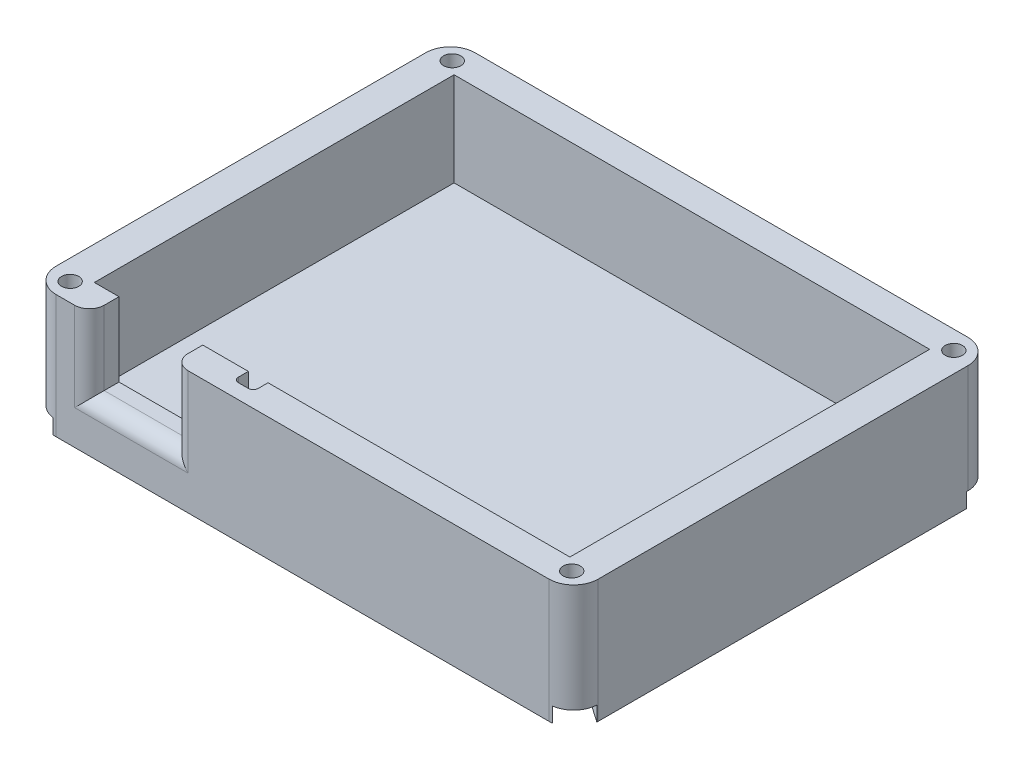
SolidWorks part; units mm, degrees
ref_plane "Front Plane" through (0, 0, 0) normal (0, 0, 1) x (1, 0, 0)
ref_plane "Top Plane" through (0, 0, 0) normal (0, 1, 0) x (1, 0, 0)
ref_plane "Right Plane" through (0, 0, 0) normal (1, 0, 0) x (0, 0, -1)
sketch "Sketch1" plane through (0, 0, 0) normal (0, 1, 0) x (1, 0, 0)
  line L1 (-55, 42.5) -> (55, 42.5)
  line L2 (-55, 42.5) -> (-55, -42.5)
  line L3 (-55, -42.5) -> (55, -42.5)
  line L4 (55, 42.5) -> (55, -42.5)
  line L5 (-55, 42.5) -> (55, -42.5) construction
  line L6 (-55, -42.5) -> (55, 42.5) construction
  point P0 (0, 0)
  dimension "D1" = 85
  dimension "D2" = 110
extrude "Base" add sketch "Sketch1" along normal blind 25
fillet "Fillet1" radius 5 4 edges at (-55, 12.5, -42.5) (55, 12.5, 42.5) (55, 12.5, -42.5) (-55, 12.5, 42.5)
sketch "Sketch2" plane through (0, 25, 0) normal (0, 1, 0) x (1, 0, 0)
  line L1 (-48.25, 36.5) -> (48.25, 36.5)
  line L2 (-48.25, 36.5) -> (-48.25, -36.5)
  line L3 (-48.25, -36.5) -> (48.25, -36.5)
  line L4 (48.25, 36.5) -> (48.25, -36.5)
  line L5 (-48.25, 36.5) -> (48.25, -36.5) construction
  line L6 (-48.25, -36.5) -> (48.25, 36.5) construction
  point P0 (0, 0)
  dimension "D1" = 73
  dimension "D2" = 96.5
extrude "Basket" cut sketch "Sketch2" against normal blind 19
sketch "Sketch3" plane through (0, 25, 0) normal (0, 1, 0) x (1, 0, 0)
  line L0 (-55, -12.0792) -> (-15, -12.0792) construction
  line L1 (-55, 37.5) -> (-55, -37.5) construction
  line L2 (-15, -12.0792) -> (-15, -36.5) construction
  line L3 (-48.25, -36.5) -> (48.25, -36.5) construction
  line L4 (-48.25, 36.5) -> (-48.25, -36.5) construction
  line L5 (-17, -33.5) -> (-13, -33.5)
  line L6 (-17, -33.5) -> (-17, -39.5)
  line L7 (-17, -39.5) -> (-13, -39.5)
  line L8 (-13, -33.5) -> (-13, -39.5)
  line L9 (-17, -33.5) -> (-13, -39.5) construction
  line L10 (-17, -39.5) -> (-13, -33.5) construction
  dimension "D2" = 4
  dimension "D3" = 6
  dimension "D4" = 33.25
extrude "Wire Channel" cut sketch "Sketch3" against normal up to surface (19 mm away) up to face at (0, 6, 0)
fillet "Wire Channel Rounding" radius 1 2 edges at (-13, 15.5, 39.5) (-17, 15.5, 39.5)
ref_plane "Battery Pack Left Side Wall" through (-48.25, 0, 0) normal (1, 0, 0) x (0, 0, -1)
sketch "Sketch5" plane through (0, 0, 42.5) normal (0, 0, 1) x (1, 0, 0)
  line L0 (-48.25, 25) -> (-43.25, 25) construction
  line L1 (-48.25, -9.9) -> (-48.25, 9.9) construction
  line L2 (-50, 25) -> (50, 25) construction
  line L5 (-43.25, 25) -> (-26.25, 25)
  line L6 (-43.25, 25) -> (-43.25, 10)
  line L7 (-43.25, 10) -> (-26.25, 10)
  line L8 (-26.25, 25) -> (-26.25, 10)
  dimension "D1" = 5
  dimension "D3" = 17
  dimension "D4" = 15
extrude "Switch Cut-out" cut sketch "Sketch5" against normal up to next
fillet "Switch Cut-out Rounding" radius 3 3 edges at (-43.25, 17.5, 42.5) (-34.75, 10, 42.5) (-26.25, 17.5, 42.5)
sketch "Sketch14" plane through (0, 25, 0) normal (0, 1, 0) x (1, 0, 0)
  line L0 (-53.5355, 41.0355) -> (-48.25, 36.5) construction
  line L1 (53.5355, 41.0355) -> (48.25, 36.5) construction
  line L2 (53.5355, -41.0355) -> (48.25, -36.5) construction
  line L3 (-53.5355, -41.0355) -> (-48.25, -36.5) construction
  arc A0 (-50, 42.5) -> (-55, 37.5) centre (-50, 37.5) ccw construction
  arc A1 (55, 37.5) -> (50, 42.5) centre (50, 37.5) ccw construction
  arc A2 (50, -42.5) -> (55, -37.5) centre (50, -37.5) ccw construction
  arc A3 (-55, -37.5) -> (-50, -42.5) centre (-50, -37.5) ccw construction
  circle A4 centre (-50.8928, 38.7678) radius 1.75
  circle A5 centre (50.8928, 38.7678) radius 1.75
  circle A6 centre (50.8928, -38.7678) radius 1.75
  circle A7 centre (-50.8928, -38.7678) radius 1.75
  point P32 (0, 0)
  point P33 (0, 0)
  point P34 (0, 0)
  point P36 (0, 0)
  point P37 (0, 0)
  point P41 (49.0124, -35.7644)
  point P42 (48.6637, -36.803)
  dimension "D1" = 3.5
  dimension "D2" = 77.5355
  dimension "D3" = 101.7855
extrude "Corner Holes" cut sketch "Sketch14" against normal through all
sketch "Sketch15" plane through (0, 0, 0) normal (0, -1, 0) x (1, 0, 0)
  line L0 (-50.641, 42.3885) -> (-52.1783, 43.4161)
  line L1 (-47.6302, 40.3758) -> (-50.641, 42.3885)
  line L2 (50.596, 42.3929) -> (52.0915, 43.4278)
  line L3 (47.9017, 36.6981) -> (51.1896, 35.1426)
  line L4 (-54.1438, 37.152) -> (-51.1314, 35.1383)
  line L5 (-51.1314, 35.1383) -> (-47.8689, 36.7464)
  line L6 (-47.8689, 36.7464) -> (-47.6302, 40.3758)
  line L7 (-52.1783, 43.4161) -> (-55.727, 38.1074)
  line L8 (-55.727, 38.1074) -> (-54.1438, 37.152)
  line L9 (51.1896, 35.1426) -> (54.1807, 37.2122)
  line L10 (-50.5474, 42.4498) -> (-53.8646, 40.8148) [skipped]
  line L11 (-53.9089, 40.9079) -> (-54.1515, 37.2176) [skipped]
  line L12 (54.1678, -36.6991) -> (55.7428, -37.6084)
  line L13 (54.1678, -36.6991) -> (50.8928, -34.8083)
  line L14 (54.1807, 37.2122) -> (53.8839, 40.8374) construction
  line L15 (53.8839, 40.8374) -> (50.596, 42.3929) construction
  line L16 (50.596, 42.3929) -> (47.6049, 40.3233)
  line L17 (47.6049, 40.3233) -> (47.9017, 36.6981)
  line L18 (50.8928, -34.8083) -> (47.4638, -36.788)
  line L19 (52.0915, 43.4278) -> (55.6762, 38.247)
  line L20 (55.6762, 38.247) -> (54.1807, 37.2122)
  line L21 (47.4638, -36.788) -> (47.4638, -40.7475)
  line L22 (47.4638, -40.7475) -> (50.7388, -42.6383)
  line L23 (-53.9527, -36.8014) -> (-55.5692, -37.6348)
  line L24 (-53.9527, -36.8014) -> (-54.1257, -40.4346) construction
  line L25 (55.7428, -37.6084) -> (52.3138, -43.5477)
  line L26 (52.3138, -43.5477) -> (50.7388, -42.6383)
  line L27 (-54.1257, -40.4346) -> (-51.0657, -42.401) construction
  line L28 (54.3218, -39.981) -> (54.3218, -36.3437) [skipped]
  line L29 (51.5566, -42.344) -> (54.7066, -40.5253) [skipped]
  line L30 (-51.0657, -42.401) -> (-47.8328, -40.7341)
  line L31 (-47.8328, -40.7341) -> (-47.6599, -37.1009)
  line L32 (-47.6599, -37.1009) -> (-50.7198, -35.1346)
  line L33 (-50.7198, -35.1346) -> (-53.9527, -36.8014)
  line L34 (-55.5692, -37.6348) -> (-52.6822, -43.2344)
  line L35 (-52.6822, -43.2344) -> (-51.0657, -42.401)
  circle A0 centre (-50.8928, 38.7678) radius 3.15 construction
  circle A1 centre (50.8928, 38.7678) radius 3.15 construction
  circle A2 centre (50.8928, -38.7678) radius 3.429 construction
  circle A3 centre (-50.8928, -38.7678) radius 3.15 construction
  dimension "D1" = 6.3
  dimension "D2" = 6.3
  dimension "D3" = 6.3
extrude "Bottom Nut Cut-out" cut sketch "Sketch15" against normal blind 3
